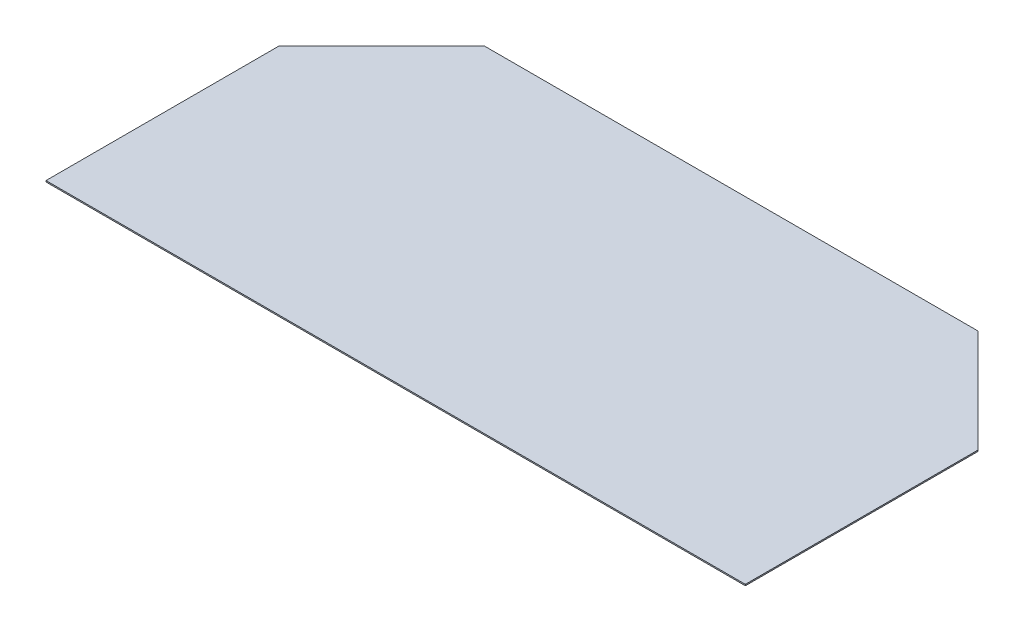
SolidWorks part; units mm, degrees
ref_plane "Front Plane" through (0, 0, 0) normal (0, 0, 1) x (1, 0, 0)
ref_plane "Top Plane" through (0, 0, 0) normal (0, 1, 0) x (1, 0, 0)
ref_plane "Right Plane" through (0, 0, 0) normal (1, 0, 0) x (0, 0, -1)
sketch "Sketch1" plane through (0, 0, 0) normal (0, 1, 0) x (1, 0, 0)
  line L0 (0, 0) -> (125, 0)
  line L1 (125, 0) -> (125, 41.58)
  line L2 (125, 41.58) -> (106.58, 60)
  line L3 (106.58, 60) -> (18.42, 60)
  line L4 (18.42, 60) -> (0, 41.58)
  line L5 (0, 41.58) -> (0, 0)
  dimension "D1" = 125
  dimension "D2" = 60
  dimension "D3" = 18.42
  dimension "D4" = 18.42
  dimension "D5" = 18.42
extrude "Boss-Extrude1" add sketch "Sketch1" along normal blind 0.23
